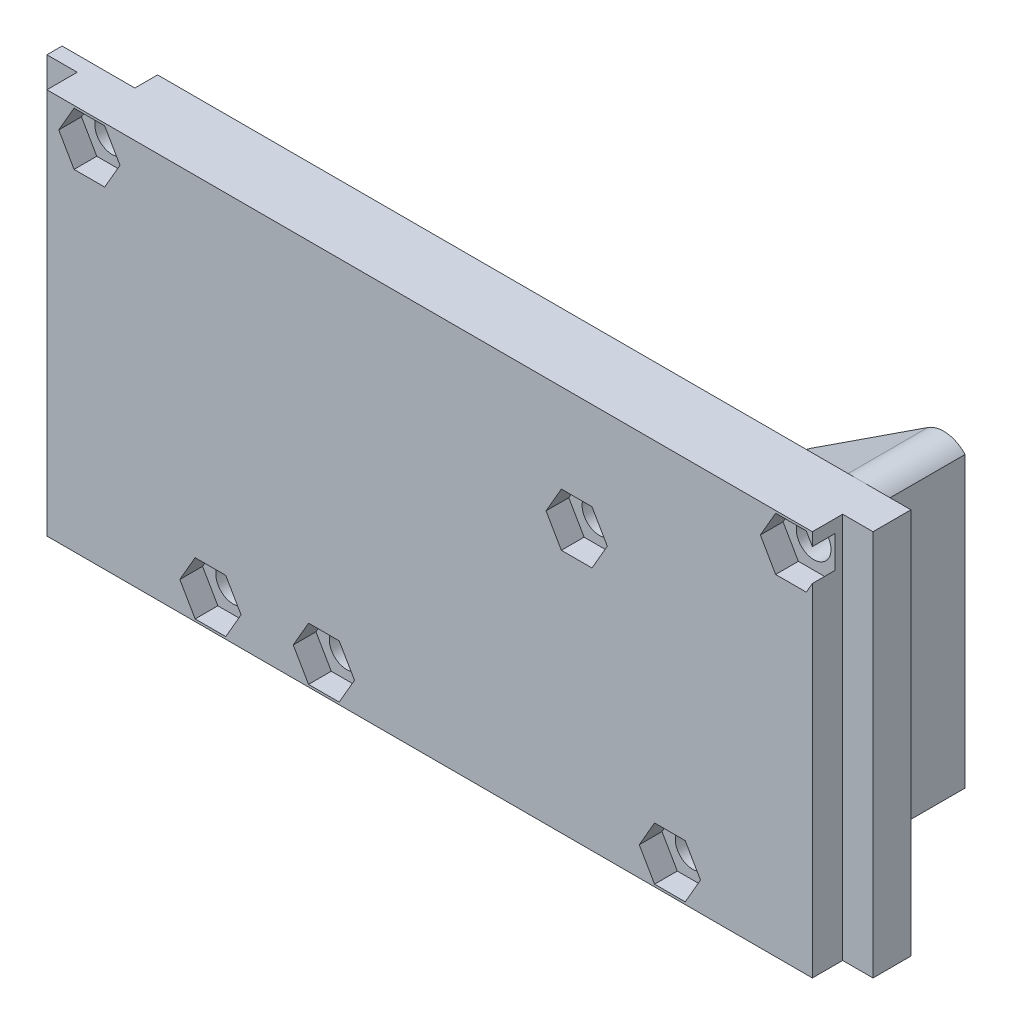
SolidWorks part; units mm, degrees
material "ABS"
ref_plane "Front Plane" through (0, 0, 0) normal (0, 0, 1) x (1, 0, 0)
ref_plane "Top Plane" through (0, 0, 0) normal (0, 1, 0) x (1, 0, 0)
ref_plane "Right Plane" through (0, 0, 0) normal (1, 0, 0) x (0, 0, -1)
sketch "Sketch2" plane through (0, 0, 0) normal (0, 1, 0) x (1, 0, 0)
  line L4 (-54.5, -58.5) -> (54.5, -58.5)
  line L8 (-54.5, -58.5) -> (-54.5, -64.5)
  line L9 (54.5, -58.5) -> (54.5, -64.5)
  line L23 (-54.5, -64.5) -> (54.5, -64.5)
extrude "Boss-Extrude2" add sketch "Sketch2" along normal blind 54
sketch "Sketch30" plane through (0, 0, 58.5) normal (0, 0, -1) x (-1, 0, 0)
  line L1 (54.5, 55) -> (-54.5, 55)
  line L2 (54.5, 55) -> (54.5, 3)
  line L3 (54.5, 3) -> (-54.5, 3)
  line L4 (-54.5, 55) -> (-54.5, 3)
  line L5 (48.5534, 51.2643) -> (53.7862, 33.4598) construction
  line L6 (27.2821, 43.2202) -> (42.8125, 53.3785) construction
  line L7 (25.2676, 5.7357) -> (20.0348, 23.5402) construction
  line L8 (46.5389, 13.7798) -> (31.0085, 3.6215) construction
  line L9 (-20.0651, 19.881) -> (-23.1574, 38.1791) construction
  line L10 (-18.9219, 42.5938) -> (-0.5115, 40.2621) construction
  line L11 (14.622, 25.743) -> (17.7143, 7.4449) construction
  line L12 (13.4789, 3.0302) -> (-4.9316, 5.3619) construction
  line L13 (48.5534, 51.2643) -> (53.7862, 33.4598)
  line L14 (27.2821, 43.2202) -> (42.8125, 53.3785)
  line L15 (26.0716, 3) -> (10.7886, 55)
  line L16 (46.5389, 13.7798) -> (30.0583, 3)
  line L17 (-20.0651, 19.881) -> (-23.1574, 38.1791)
  line L18 (-18.9219, 42.5938) -> (-0.5115, 40.2621)
  line L19 (14.622, 25.743) -> (18.4655, 3)
  line L20 (13.7173, 3) -> (-4.9316, 5.3619)
  line L22 (20.0348, 3) -> (12.801, 3) construction
  line L23 (13.7173, 3) -> (18.4655, 3)
  line L24 (23.0228, 3) -> (32.4348, 3) construction
  line L25 (26.0716, 3) -> (30.0583, 3)
  line L26 (54.2135, 31.6616) -> (54.5, 31.6616)
  line L27 (54.3117, 25.9329) -> (54.5, 25.9467)
  arc A0 (48.5534, 51.2643) -> (42.8125, 53.3785) centre (44.898, 50.19) ccw construction
  arc A1 (46.5389, 13.7798) -> (53.7862, 33.4598) centre (36.9105, 28.5) ccw construction
  arc A2 (27.2821, 43.2202) -> (20.0348, 23.5402) centre (36.9105, 28.5) ccw construction
  arc A4 (-18.9219, 42.5938) -> (-23.1574, 38.1791) centre (-19.4007, 38.814) ccw construction
  arc A5 (14.622, 25.743) -> (-0.5115, 40.2621) centre (-2.7215, 22.812) ccw construction
  arc A7 (-20.0651, 19.881) -> (-4.9316, 5.3619) centre (-2.7215, 22.812) ccw construction
  arc A8 (48.5534, 51.2643) -> (42.8125, 53.3785) centre (44.898, 50.19) ccw
  arc A9 (46.5389, 13.7798) -> (53.7862, 33.4598) centre (36.9105, 28.5) ccw
  arc A10 (27.2821, 43.2202) -> (20.0348, 23.5402) centre (36.9105, 28.5) ccw
  arc A12 (-18.9219, 42.5938) -> (-23.1574, 38.1791) centre (-19.4007, 38.814) ccw
  arc A13 (14.622, 25.743) -> (-0.5115, 40.2621) centre (-2.7215, 22.812) ccw
  arc A15 (-20.0651, 19.881) -> (-4.9316, 5.3619) centre (-2.7215, 22.812) ccw
extrude "Boss-Extrude18" add sketch "Sketch30" along normal blind 3
sketch "Sketch26" plane through (0, 0, 58.5) normal (0, 0, -1) x (-1, 0, 0)
  line L0 (-35.0379, 3) -> (-26.4738, 3) construction
  line L2 (-32.8358, 3) -> (-28.8491, 3)
  line L3 (-50.5, 52.7471) -> (-50.5, 14.6259)
  line L4 (-28.0451, 5.7357) -> (-22.8123, 23.5402)
  line L5 (-49.3164, 13.7798) -> (-33.786, 3.6215)
  line L6 (-51.3309, 51.2643) -> (-56.5637, 33.4598)
  line L7 (-30.0596, 43.2202) -> (-45.59, 53.3785)
  line L8 (-28.8491, 3) -> (-22.8123, 23.5402)
  line L9 (-49.3164, 13.7798) -> (-32.8358, 3)
  line L10 (-51.3309, 51.2643) -> (-56.5637, 33.4598)
  line L11 (-30.0596, 43.2202) -> (-45.59, 53.3785)
  line L12 (-54.5, 54) -> (-54.5, 3) construction
  arc A4 (-33.786, 3.6215) -> (-28.0451, 5.7357) centre (-31.7005, 6.81) ccw
  arc A5 (-56.5637, 33.4598) -> (-49.3164, 13.7798) centre (-39.688, 28.5) ccw
  arc A6 (-45.59, 53.3785) -> (-51.3309, 51.2643) centre (-47.6755, 50.19) ccw
  arc A7 (-22.8123, 23.5402) -> (-30.0596, 43.2202) centre (-39.688, 28.5) ccw
  arc A9 (-56.5637, 33.4598) -> (-49.3164, 13.7798) centre (-39.688, 28.5) ccw
  arc A10 (-45.59, 53.3785) -> (-51.3309, 51.2643) centre (-47.6755, 50.19) ccw
  arc A11 (-22.8123, 23.5402) -> (-30.0596, 43.2202) centre (-39.688, 28.5) ccw
  point P20 (0, 0)
  point P21 (0, 0)
  line M37 (13.7173, 3) -> (-54.5, 3)
  dimension "D2" = 4
  dimension "D1" = 0
extrude "Boss-Extrude14" add sketch "Sketch26" along normal blind 14.15 contours L8 A11 L11 A10 L10 L3 A9 L9 M37
sketch "Sketch9" plane through (0, 0, 64.5) normal (0, 0, 1) x (1, 0, 0)
  arc A24 (-42.7529, 50.98) -> (-47.0432, 49.4) centre (-44.898, 50.19) ccw construction
  arc A25 (-47.0432, 49.4) -> (-42.7529, 50.98) centre (-44.898, 50.19) ccw construction
  arc A26 (-42.7529, 50.98) -> (-47.0432, 49.4) centre (-44.898, 50.19) ccw
  arc A27 (-47.0432, 49.4) -> (-42.7529, 50.98) centre (-44.898, 50.19) ccw
  arc A28 (-31.0681, 6.02) -> (-26.7778, 7.6) centre (-28.923, 6.81) ccw construction
  arc A29 (-26.7778, 7.6) -> (-31.0681, 6.02) centre (-28.923, 6.81) ccw construction
  arc A30 (-31.0681, 6.02) -> (-26.7778, 7.6) centre (-28.923, 6.81) ccw
  arc A31 (-26.7778, 7.6) -> (-31.0681, 6.02) centre (-28.923, 6.81) ccw
  arc A32 (-15.5402, 8.4596) -> (-12.375, 5.1604) centre (-13.9576, 6.81) ccw construction
  arc A33 (-12.375, 5.1604) -> (-15.5402, 8.4596) centre (-13.9576, 6.81) ccw construction
  arc A34 (-15.5402, 8.4596) -> (-12.375, 5.1604) centre (-13.9576, 6.81) ccw
  arc A35 (-12.375, 5.1604) -> (-15.5402, 8.4596) centre (-13.9576, 6.81) ccw
  arc A36 (20.9833, 37.1644) -> (17.818, 40.4636) centre (19.4007, 38.814) ccw construction
  arc A37 (17.818, 40.4636) -> (20.9833, 37.1644) centre (19.4007, 38.814) ccw construction
  arc A38 (20.9833, 37.1644) -> (17.818, 40.4636) centre (19.4007, 38.814) ccw
  arc A39 (17.818, 40.4636) -> (20.9833, 37.1644) centre (19.4007, 38.814) ccw
  arc A40 (29.5553, 7.6) -> (33.8456, 6.02) centre (31.7005, 6.81) ccw construction
  arc A41 (33.8456, 6.02) -> (29.5553, 7.6) centre (31.7005, 6.81) ccw construction
  arc A42 (29.5553, 7.6) -> (33.8456, 6.02) centre (31.7005, 6.81) ccw
  arc A43 (33.8456, 6.02) -> (29.5553, 7.6) centre (31.7005, 6.81) ccw
  arc A44 (49.8207, 49.4) -> (45.5304, 50.98) centre (47.6755, 50.19) ccw construction
  arc A45 (45.5304, 50.98) -> (49.8207, 49.4) centre (47.6755, 50.19) ccw construction
  arc A46 (49.8207, 49.4) -> (45.5304, 50.98) centre (47.6755, 50.19) ccw
  arc A47 (45.5304, 50.98) -> (49.8207, 49.4) centre (47.6755, 50.19) ccw
extrude "Cut-Extrude7" cut sketch "Sketch9" against normal blind 23
sketch "Sketch24" plane through (0, 0, 64.5) normal (0, 0, 1) x (1, 0, 0)
  line L7 (-40.8566, 50.19) -> (-42.8773, 53.69)
  line L8 (-42.8773, 53.69) -> (-46.9188, 53.69)
  line L9 (-46.9188, 53.69) -> (-48.9395, 50.19)
  line L10 (-48.9395, 50.19) -> (-46.9188, 46.69)
  line L11 (-46.9188, 46.69) -> (-42.8773, 46.69)
  line L12 (-42.8773, 46.69) -> (-40.8566, 50.19)
  line L13 (51.717, 50.19) -> (49.6963, 53.69)
  line L14 (49.6963, 53.69) -> (45.6548, 53.69)
  line L15 (45.6548, 53.69) -> (43.6341, 50.19)
  line L16 (43.6341, 50.19) -> (45.6548, 46.69)
  line L17 (45.6548, 46.69) -> (49.6963, 46.69)
  line L18 (49.6963, 46.69) -> (51.717, 50.19)
  line L19 (35.7419, 6.81) -> (33.7212, 10.31)
  line L20 (33.7212, 10.31) -> (29.6797, 10.31)
  line L21 (29.6797, 10.31) -> (27.659, 6.81)
  line L22 (27.659, 6.81) -> (29.6797, 3.31)
  line L23 (29.6797, 3.31) -> (33.7212, 3.31)
  line L24 (33.7212, 3.31) -> (35.7419, 6.81)
  line L25 (-9.9161, 6.81) -> (-11.9368, 10.31)
  line L26 (-11.9368, 10.31) -> (-15.9783, 10.31)
  line L27 (-15.9783, 10.31) -> (-17.999, 6.81)
  line L28 (-17.999, 6.81) -> (-15.9783, 3.31)
  line L29 (-15.9783, 3.31) -> (-11.9368, 3.31)
  line L30 (-11.9368, 3.31) -> (-9.9161, 6.81)
  line L31 (23.4421, 38.814) -> (21.4214, 42.314)
  line L32 (21.4214, 42.314) -> (17.3799, 42.314)
  line L33 (17.3799, 42.314) -> (15.3592, 38.814)
  line L34 (15.3592, 38.814) -> (17.3799, 35.314)
  line L35 (17.3799, 35.314) -> (21.4214, 35.314)
  line L36 (21.4214, 35.314) -> (23.4421, 38.814)
  line L37 (-24.8815, 6.81) -> (-26.9022, 10.31)
  line L38 (-26.9022, 10.31) -> (-30.9437, 10.31)
  line L39 (-30.9437, 10.31) -> (-32.9644, 6.81)
  line L40 (-32.9644, 6.81) -> (-30.9437, 3.31)
  line L41 (-30.9437, 3.31) -> (-26.9022, 3.31)
  line L42 (-26.9022, 3.31) -> (-24.8815, 6.81)
  circle A1 centre (-44.898, 50.19) radius 3.5 construction
  circle A2 centre (47.6755, 50.19) radius 3.5 construction
  circle A3 centre (31.7005, 6.81) radius 3.5 construction
  circle A4 centre (-13.9576, 6.81) radius 3.5 construction
  circle A5 centre (19.4007, 38.814) radius 3.5 construction
  circle A6 centre (-28.923, 6.81) radius 3.5 construction
  dimension "D2" = 7
  dimension "D3" = 7
  dimension "D4" = 7
  dimension "D5" = 7
  dimension "D6" = 7
extrude "Cut-Extrude8" cut sketch "Sketch24" against normal blind 3
sketch "Sketch33" plane through (-54.5, 0, 0) normal (-1, 0, 0) x (0, 0, 1)
  line L1 (58.5, 3) -> (64.5, 3)
  line L2 (58.5, 3) -> (58.5, 0)
  line L3 (58.5, 0) -> (64.5, 0)
  line L4 (64.5, 3) -> (64.5, 0)
extrude "Cut-Extrude9" cut sketch "Sketch33" against normal blind 123
sketch "Sketch34" plane through (0, 54, 0) normal (0, 1, 0) x (1, 0, 0)
  line L1 (-54.5, -64.5) -> (-50.5, -64.5)
  line L2 (-54.5, -64.5) -> (-54.5, -60.5)
  line L3 (-54.5, -60.5) -> (-50.5, -60.5)
  line L4 (-50.5, -64.5) -> (-50.5, -60.5)
  line L9 (54.5, -64.5) -> (50.5, -64.5)
  line L10 (54.5, -64.5) -> (54.5, -60.5)
  line L11 (54.5, -60.5) -> (50.5, -60.5)
  line L12 (50.5, -64.5) -> (50.5, -60.5)
  dimension "D1" = 4
  dimension "D2" = 4
  dimension "D3" = 4
  dimension "D4" = 4
extrude "Cut-Extrude10" cut sketch "Sketch34" against normal blind 86
